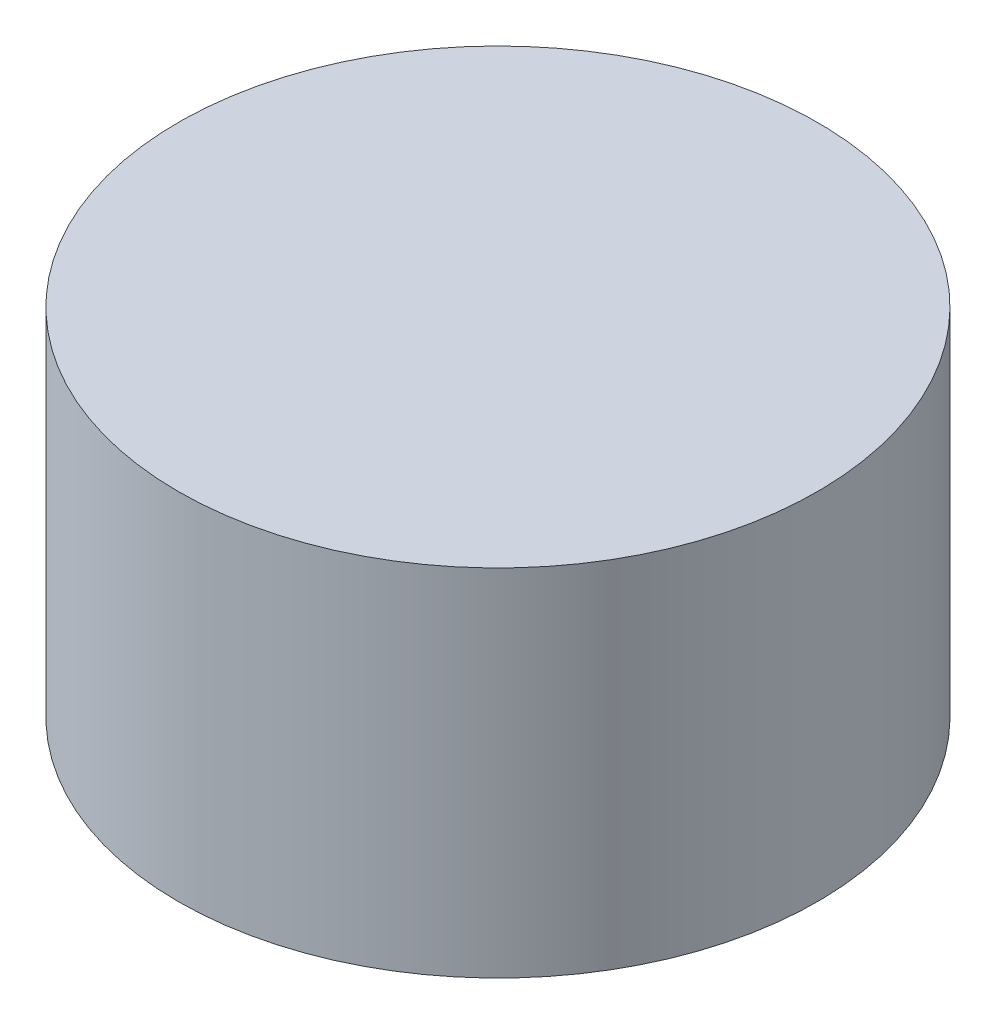
SolidWorks part; units mm, degrees
ref_plane "Front Plane" through (0, 0, 0) normal (0, 0, 1) x (1, 0, 0)
ref_plane "Top Plane" through (0, 0, 0) normal (0, 1, 0) x (1, 0, 0)
ref_plane "Right Plane" through (0, 0, 0) normal (1, 0, 0) x (0, 0, -1)
sketch "Sketch1" plane through (0, 0, 0) normal (0, 1, 0) x (1, 0, 0)
  circle A0 centre (0, 0) radius 45
  dimension "D1" = 90
extrude "Boss-Extrude1" add sketch "Sketch1" along normal blind 50
